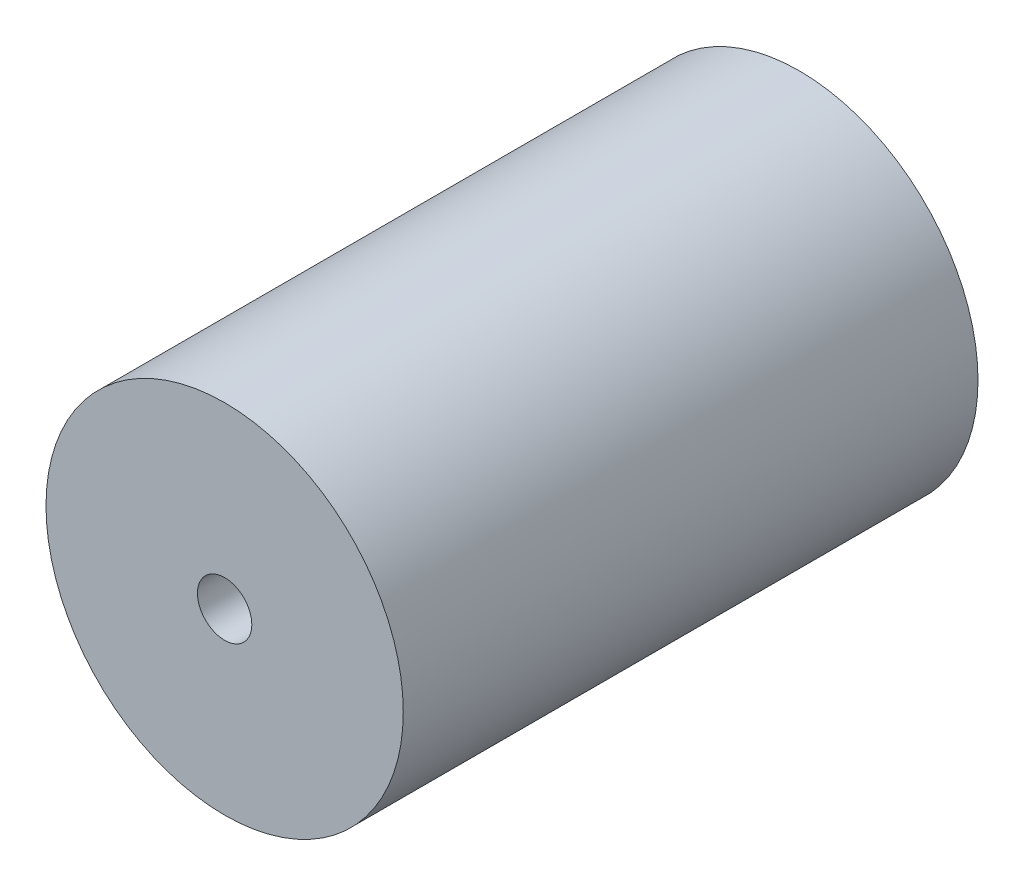
SolidWorks part; units mm, degrees
ref_plane "Front Plane" through (0, 0, 0) normal (0, 0, 1) x (1, 0, 0)
ref_plane "Top Plane" through (0, 0, 0) normal (0, 1, 0) x (1, 0, 0)
ref_plane "Right Plane" through (0, 0, 0) normal (1, 0, 0) x (0, 0, -1)
sketch "Sketch1" plane through (0, 0, 0) normal (0, 0, 1) x (1, 0, 0)
  circle A0 centre (0, 0) radius 11.5
  dimension "D1" = 23
extrude "Boss-Extrude1" add sketch "Sketch1" along normal blind 37
sketch "Sketch2" plane through (0, 0, 37) normal (0, 0, 1) x (1, 0, 0)
  circle A0 centre (0, 0) radius 1.75
  dimension "D1" = 3.5
extrude "Cut-Extrude1" cut sketch "Sketch2" against normal through all
